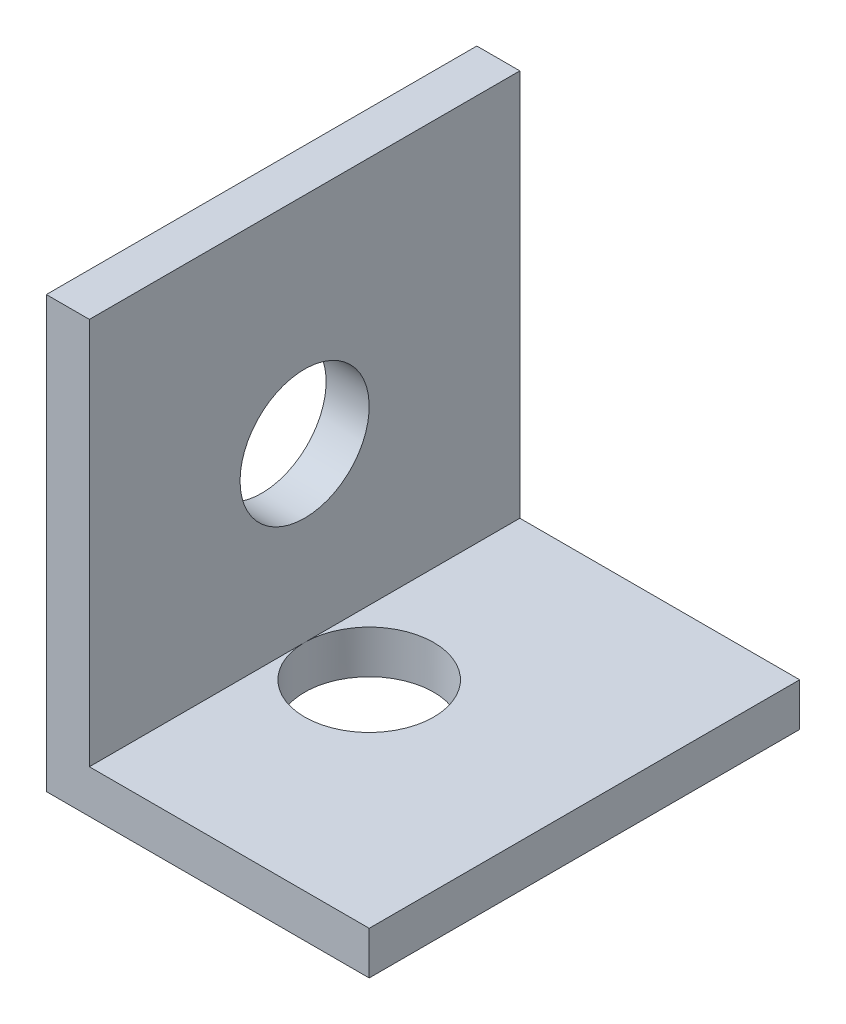
SolidWorks part; units mm, degrees
ref_plane "前视基准面" through (0, 0, 0) normal (0, 0, 1) x (1, 0, 0)
ref_plane "上视基准面" through (0, 0, 0) normal (0, 1, 0) x (1, 0, 0)
ref_plane "右视基准面" through (0, 0, 0) normal (1, 0, 0) x (0, 0, -1)
sketch "草图1" plane through (0, 0, 0) normal (0, 0, 1) x (1, 0, 0)
  line L0 (0, 0) -> (0, 20)
  line L1 (0, 20) -> (2, 20)
  line L2 (2, 20) -> (2, 2)
  line L3 (2, 2) -> (15, 2)
  line L4 (15, 2) -> (15, 0)
  line L5 (15, 0) -> (0, 0)
  dimension "D1" = 2
  dimension "D2" = 15
  dimension "D3" = 20
extrude "凸台-拉伸1" add sketch "草图1" along normal mid plane 20
sketch "草图2" plane through (0, 0, 0) normal (-1, 0, 0) x (0, 0, 1)
  line L0 (10, 20) -> (-10, 20) construction
  circle A0 centre (0, 10) radius 3
  point P4 (0, 20)
  dimension "D2" = 6
  dimension "D1" = 10
extrude "切除-拉伸1" cut sketch "草图2" against normal up to surface (2 mm away) up to face at (2, 11, 0)
sketch "草图3" plane through (0, 0, 0) normal (0, -1, 0) x (1, 0, 0)
  line L0 (15, 10) -> (15, -10) construction
  circle A0 centre (5, 0) radius 3
  point P4 (15, 0)
  dimension "D2" = 6
  dimension "D1" = 10
extrude "切除-拉伸2" cut sketch "草图3" against normal up to surface (2 mm away) up to face at (8.5, 2, 0)
